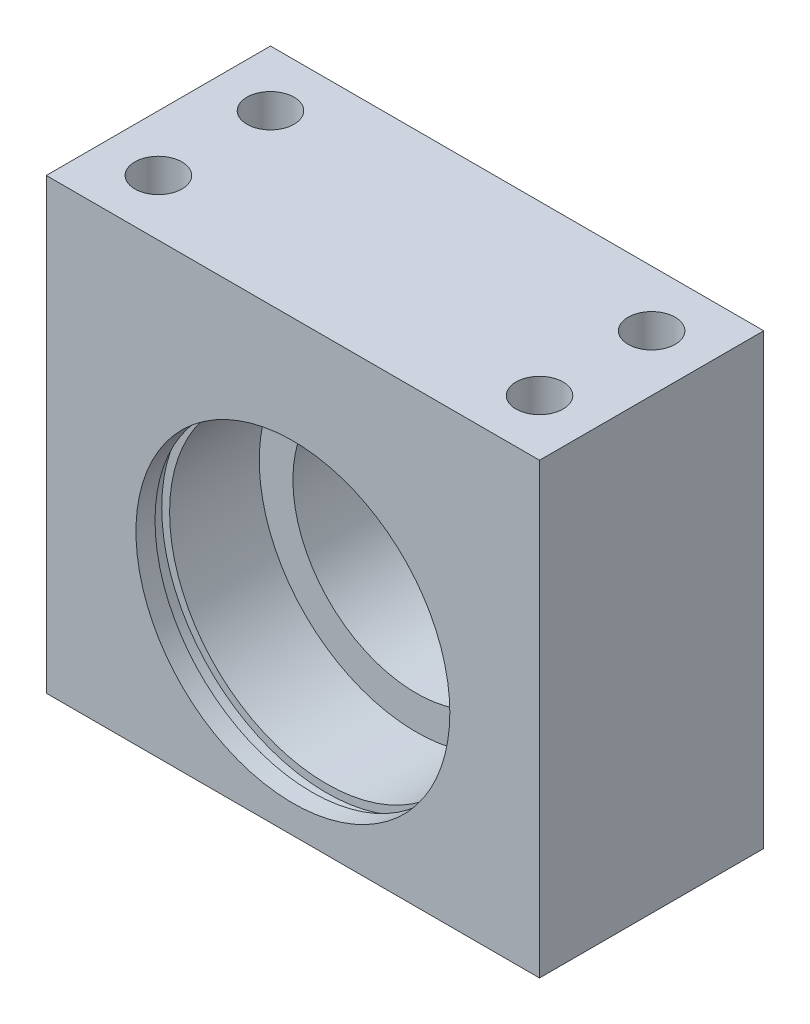
SolidWorks part; units mm, degrees
material "1.0037 (S235JR)"
ref_plane "Płaszczyzna przednia" through (0, 0, 0) normal (0, 0, 1) x (1, 0, 0)
ref_plane "Płaszczyzna górna" through (0, 0, 0) normal (0, 1, 0) x (1, 0, 0)
ref_plane "Płaszczyzna prawa" through (0, 0, 0) normal (1, 0, 0) x (0, 0, -1)
sketch "Szkic1" plane through (0, 0, 0) normal (0, 1, 0) x (1, 0, 0)
  line L1 (-22, -10) -> (22, -10)
  line L2 (-22, -10) -> (-22, 10)
  line L3 (-22, 10) -> (22, 10)
  line L4 (22, -10) -> (22, 10)
  line L5 (-22, -10) -> (22, 10) construction
  line L6 (-22, 10) -> (22, -10) construction
  point P0 (0, 0)
  dimension "D1" = 20
  dimension "D2" = 44
extrude "Dodanie-wyciągnięcie1" add sketch "Szkic1" along normal blind 40
sketch "Szkic3" plane through (0, 0, 10) normal (0, 0, 1) x (1, 0, 0)
  line L0 (0, 40) -> (0, 0) construction
  line L1 (-22, 40) -> (22, 40) construction
  line L2 (-22, 0) -> (22, 0) construction
  circle A0 centre (0, 16.5) radius 11
  dimension "D1" = 22
  dimension "D2" = 16.5
extrude "Wytnij-wyciągnięcie2" cut sketch "Szkic3" against normal through all
sketch "Szkic4" plane through (0, 0, 10) normal (0, 0, 1) x (1, 0, 0)
  circle A0 centre (0, 16.5) radius 14
  dimension "D1" = 28
extrude "Wytnij-wyciągnięcie3" cut sketch "Szkic4" against normal blind 11
sketch "Szkic5" plane through (0, 0, 0) normal (1, 0, 0) x (0, 0, -1)
  line L0 (-10, 2.5) -> (1, 2.5) construction
  line L1 (-7, 2.5) -> (-8.3, 2.5)
  line L2 (-7, 2.5) -> (-7, 1.8)
  line L3 (-7, 1.8) -> (-8.3, 1.8)
  line L4 (-8.3, 2.5) -> (-8.3, 1.8)
  line L6 (-9.2946, 16.5) -> (-18.2923, 16.5) construction
  line L7 (-10, 30.5) -> (-10, 2.5) construction
  dimension "D1" = 1.3
  dimension "D2" = 14.7
  dimension "D3" = 3
  dimension "D4" = 16.5
sketch "Szkic6" plane through (0, 40, 0) normal (0, 1, 0) x (1, 0, 0)
  line L10 (17, -5) -> (17, 5)
  line L11 (17, 5) -> (-17, 5)
  line L12 (-17, 5) -> (-17, -5)
  line L13 (-17, -5) -> (17, -5)
  line L14 (17, -5) -> (17, 5)
  line L15 (17, 5) -> (-17, 5)
  line L16 (-17, 5) -> (-17, -5)
  line L17 (-17, -5) -> (17, -5)
  dimension "D1" = 5
hole_wizard "Otwór gwintowany M5x0.81" positions "Szkic8" profile "Szkic7" tap size "M5x0.8" standard "Ansi Metric"
sketch "Szkic8" plane through (0, 40, 0) normal (0, 1, 0) x (1, 0, 0)
  point P0 (17, 5)
  point P3 (17, -5)
  point P6 (-17, -5)
  point P9 (-17, 5)
sketch "Szkic7" plane through (17, 40, -5) normal (1, 0, 0) x (0, 0, 1)
  line L0 (0, 0) -> (0, 26.2618)
  line L1 (0, 26.2618) -> (2.1, 25)
  line L2 (2.1, 25) -> (2.1, 0)
  line L5 (2.1, 0) -> (0, 0)
  line L10 (0, 26.2618) -> (-2.1, 25) construction
  line L11 (0, -6.35) -> (0, 107.95) construction
  dimension "Średnica wiertła gwintu" = 4.2
  dimension "Głębokość otworu gwintowanego" = 25
  dimension "Kąt wiertła" = 118
revolve "Wycięcie-obrót1" cut sketch "Szkic5" angle 360 about L6
sketch "Szkic9" plane through (0, 0, 10) normal (0, 0, 1) x (1, 0, 0)
  line L0 (10.5748, 40) -> (22, 32)
  line L1 (-22, 40) -> (22, 40) construction
  line L2 (22, 40) -> (22, 0) construction
  line L3 (-22, 32) -> (-10.5748, 40)
  line L4 (-22, 40) -> (-22, 0) construction
  line M3 (22, 0) -> (22, 40)
  line M4 (22, 40) -> (-22, 40)
  line M5 (-22, 40) -> (-22, 0)
  dimension "D1" = 8
  dimension "D2" = 35
extrude "Wytnij-wyciągnięcie5" [suppressed] cut sketch "Szkic9" against normal through all contours L3 M5 M4 | L0 M4 M3
